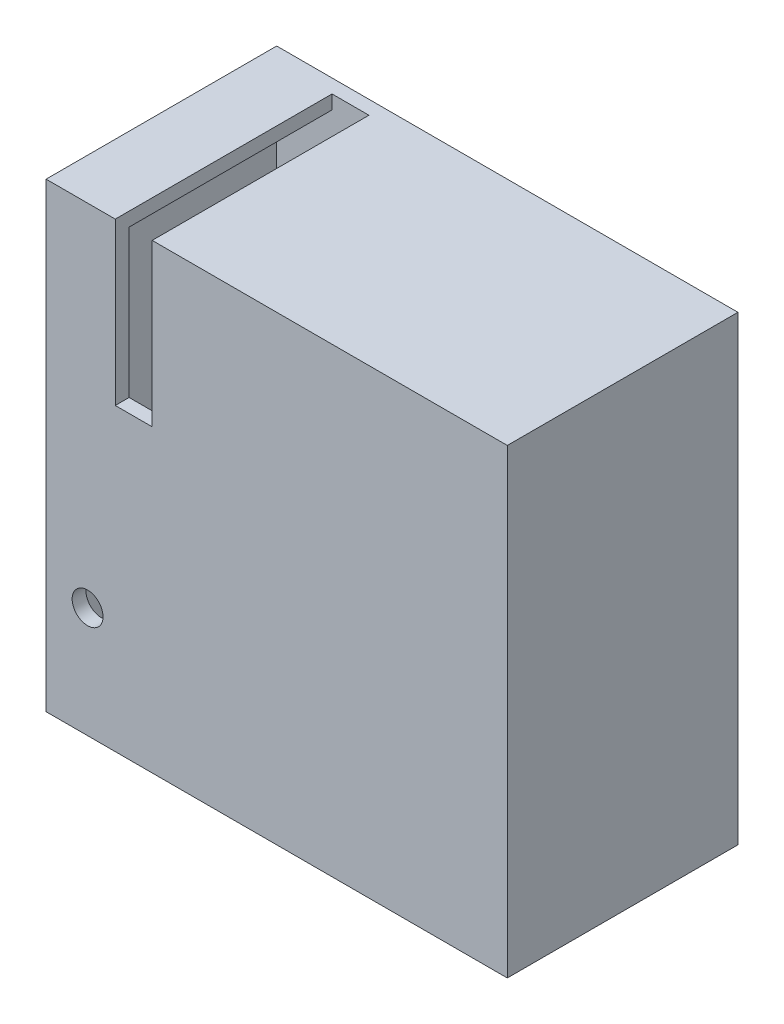
SolidWorks part; units mm, degrees
ref_plane "Front Plane" through (0, 0, 0) normal (0, 0, 1) x (1, 0, 0)
ref_plane "Top Plane" through (0, 0, 0) normal (0, 1, 0) x (1, 0, 0)
ref_plane "Right Plane" through (0, 0, 0) normal (1, 0, 0) x (0, 0, -1)
sketch "Sketch1" plane through (0, 0, 0) normal (0, 0, 1) x (1, 0, 0)
  line L1 (0, 0) -> (100, 0)
  line L2 (0, 0) -> (0, 100)
  line L3 (0, 100) -> (100, 100)
  line L4 (100, 0) -> (100, 100)
  dimension "D1" = 100
  dimension "D2" = 100
extrude "Boss-Extrude2" add sketch "Sketch1" against normal blind 50
sketch "Sketch3" plane through (0, 0, 0) normal (0, 0, 1) x (1, 0, 0)
  line L0 (100, 100) -> (0, 100) construction
  line L1 (15, 100) -> (23, 100)
  line L2 (15, 100) -> (15, 65)
  line L3 (15, 65) -> (23, 65)
  line L4 (23, 100) -> (23, 65)
  line L5 (0, 100) -> (0, 0) construction
  dimension "D1" = 8
  dimension "D2" = 15
  dimension "D3" = 35
extrude "Cut-Extrude2" cut sketch "Sketch3" against normal offset from surface (47 mm away) 3 up to face at (50, 50, -50)
sketch "Sketch4" plane through (0, 0, 0) normal (0, -1, 0) x (1, 0, 0)
  line L0 (0, 0) -> (100, 0) construction
  line L1 (3, -3) -> (97, -3)
  line L2 (3, -3) -> (3, -47)
  line L3 (3, -47) -> (97, -47)
  line L4 (97, -3) -> (97, -47)
  line L5 (0, -50) -> (0, 0) construction
  line L6 (0, -50) -> (100, -50) construction
  line L7 (100, -50) -> (100, 0) construction
  dimension "D1" = 3
  dimension "D2" = 3
  dimension "D3" = 3
  dimension "D4" = 3
extrude "Cut-Extrude3" cut sketch "Sketch4" against normal offset from surface (97 mm away) 3 up to face at (34.5, 100, -24.25)
sketch "Sketch5" plane through (0, 0, 0) normal (-1, 0, 0) x (0, 0, 1)
  line L0 (-50, 100) -> (0, 100) construction
  line L1 (-31, 28) -> (-19, 28)
  line L2 (-31, 28) -> (-31, 20)
  line L3 (-31, 20) -> (-19, 20)
  line L4 (-19, 28) -> (-19, 20)
  line L5 (-50, 0) -> (0, 0) construction
  point P6 (-25, 100)
  point P7 (-25, 28)
  dimension "D1" = 12
  dimension "D2" = 8
  dimension "D3" = 20
extrude "Cut-Extrude4" cut sketch "Sketch5" against normal up to next
sketch "Sketch6" plane through (0, 0, 0) normal (0, 0, 1) x (1, 0, 0)
  line L0 (0, 100) -> (0, 0) construction
  line L1 (3, 30) -> (15, 30) construction
  line L2 (3, 30) -> (3, 18) construction
  line L3 (3, 18) -> (15, 18) construction
  line L4 (15, 30) -> (15, 18) construction
  line L6 (0, 20) -> (0, 28) construction
  circle A0 centre (9, 24) radius 3.35
  point P6 (0, 0)
  point P7 (9, 30)
  point P8 (3, 24)
  point P15 (0, 24)
  point P16 (0, 0)
  dimension "D1" = 6.7
  dimension "D2" = 12
  dimension "D3" = 3
extrude "Cut-Extrude5" cut sketch "Sketch6" against normal up to next
